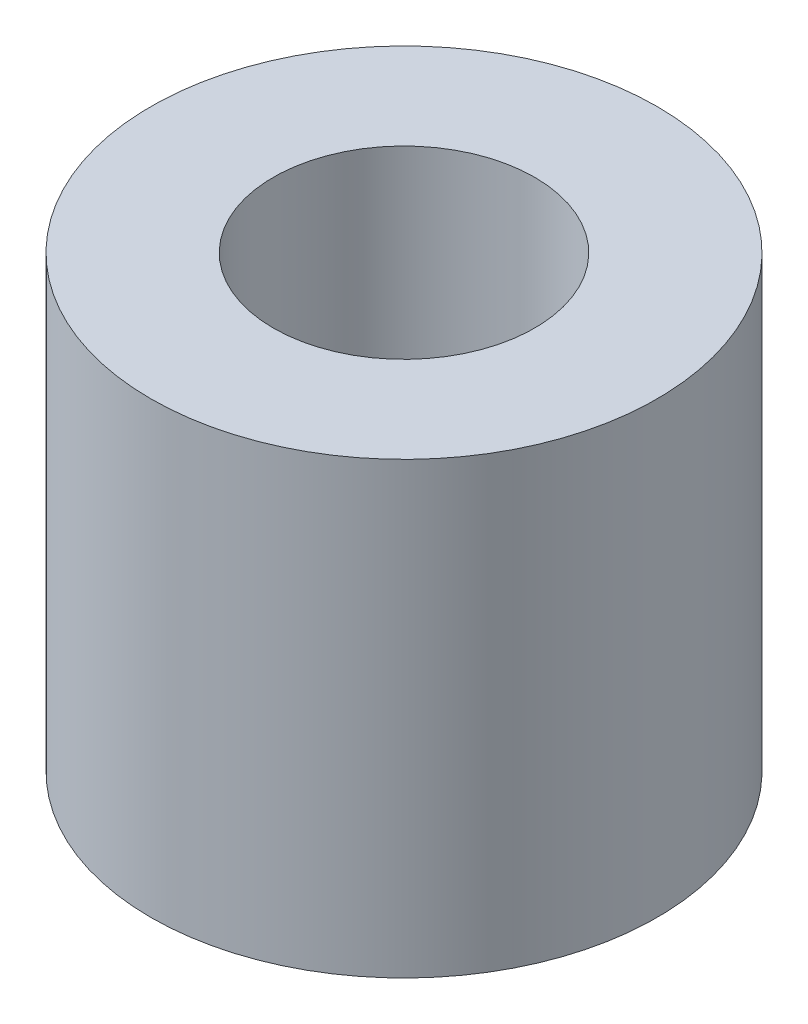
SolidWorks part; units mm, degrees
ref_plane "前视基准面" through (0, 0, 0) normal (0, 0, 1) x (1, 0, 0)
ref_plane "上视基准面" through (0, 0, 0) normal (0, 1, 0) x (1, 0, 0)
ref_plane "右视基准面" through (0, 0, 0) normal (1, 0, 0) x (0, 0, -1)
sketch "草图1" plane through (0, 0, 0) normal (0, 1, 0) x (1, 0, 0)
  circle A0 centre (0, 0) radius 1.6
  circle A1 centre (0, 0) radius 3.1
  dimension "D1" = 3.2
  dimension "D2" = 1.5
extrude "凸台-拉伸1" add sketch "草图1" along normal blind 5.5
